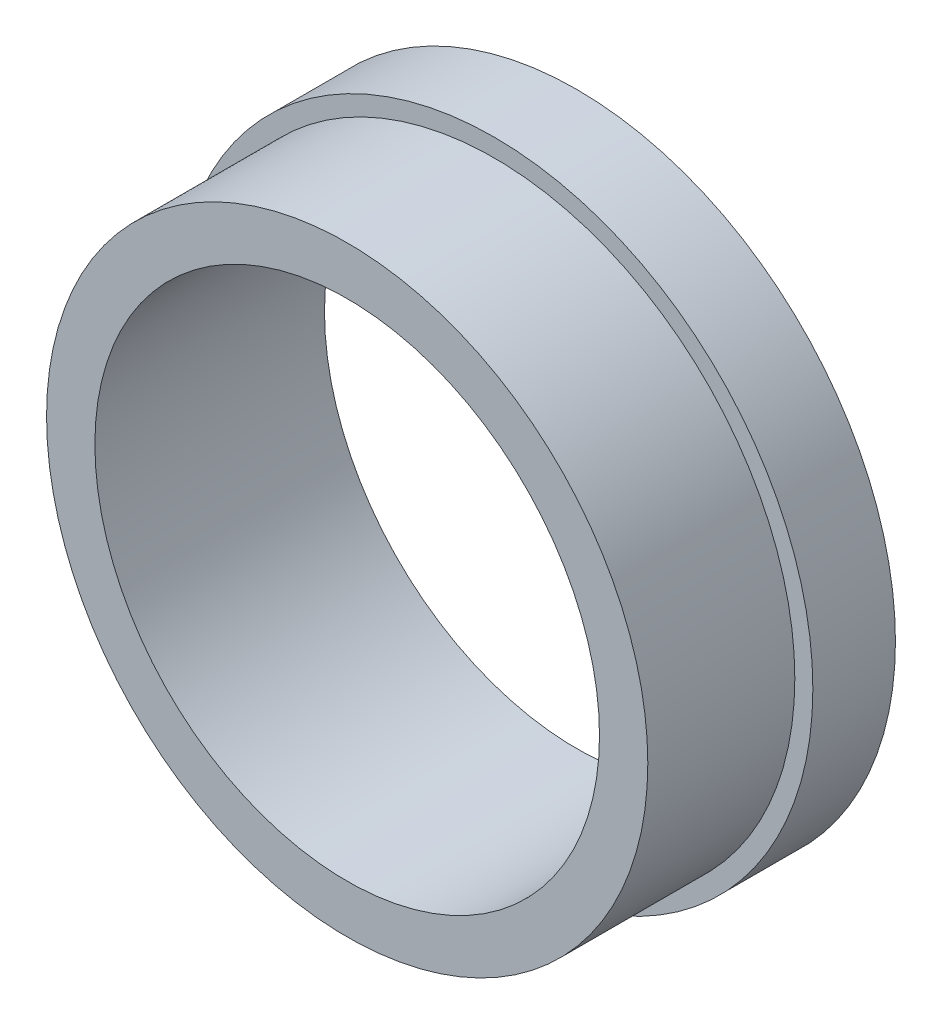
SolidWorks part; units mm, degrees
material "6061-T6 (SS)"
ref_plane "Front Plane" through (0, 0, 0) normal (0, 0, 1) x (1, 0, 0)
ref_plane "Top Plane" through (0, 0, 0) normal (0, 1, 0) x (1, 0, 0)
ref_plane "Right Plane" through (0, 0, 0) normal (1, 0, 0) x (0, 0, -1)
sketch "Sketch1" plane through (0, 0, 0) normal (0, 0, 1) x (1, 0, 0)
  circle A0 centre (0, 0) radius 49
  circle A1 centre (0, 0) radius 38.7985
  dimension "D1" = 77.597
  dimension "D2" = 98
extrude "Extrude1" add sketch "Sketch1" along normal blind 35.306
sketch "Sketch2" plane through (0, 0, 35.306) normal (0, 0, 1) x (1, 0, 0)
  circle A0 centre (0, 0) radius 46.228
extrude "Extrude2" cut sketch "Sketch2" against normal blind 22.606 flip side to cut
